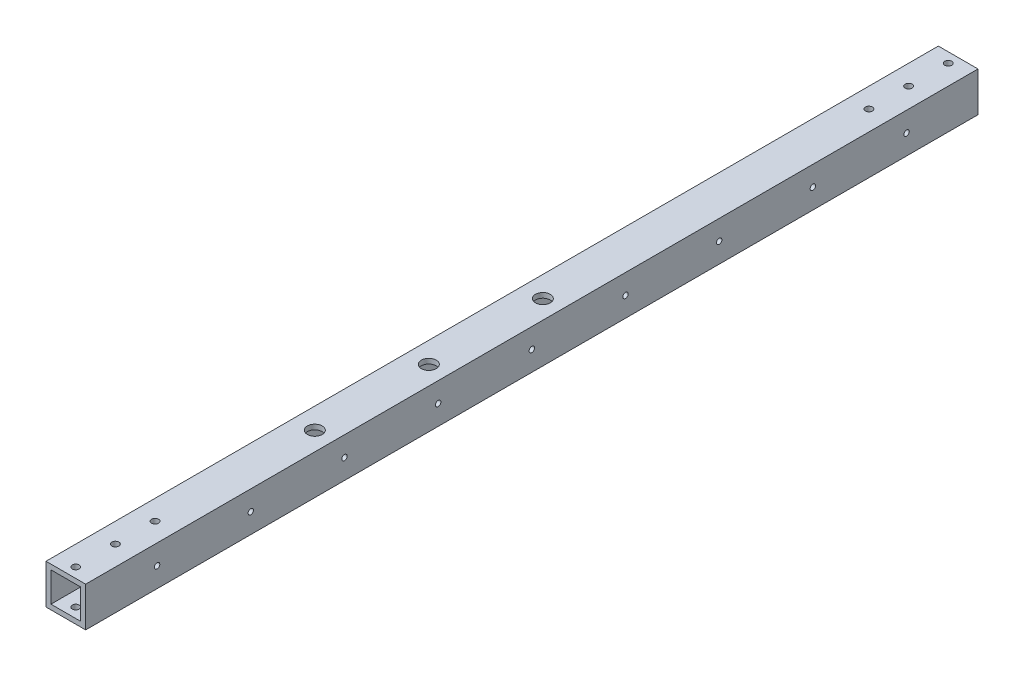
SolidWorks part; units mm, degrees
material "6061-T6 (SS)"
ref_plane "Front Plane" through (0, 0, 0) normal (0, 0, 1) x (1, 0, 0)
ref_plane "Top Plane" through (0, 0, 0) normal (0, 1, 0) x (1, 0, 0)
ref_plane "Right Plane" through (0, 0, 0) normal (1, 0, 0) x (0, 0, -1)
sketch "Sketch1" plane through (0, 0, 0) normal (0, 0, 1) x (1, 0, 0)
  line L1 (-12.7, -12.7) -> (12.7, -12.7)
  line L2 (-12.7, -12.7) -> (-12.7, 12.7)
  line L3 (-12.7, 12.7) -> (12.7, 12.7)
  line L4 (12.7, -12.7) -> (12.7, 12.7)
  line L5 (-12.7, -12.7) -> (12.7, 12.7) construction
  line L6 (-12.7, 12.7) -> (12.7, -12.7) construction
  point P0 (0, 0)
  dimension "D1" = 25.4
  dimension "D2" = 25.4
extrude "Extrude-Thin1" add sketch "Sketch1" along normal blind 571.5 thin thin type one direction reverse wall 3.175
hole_wizard "#8 Clearance Hole1" positions "3DSketch1" profile "Sketch3" hole size "#8" standard "ANSI Inch" end condition through all
sketch3d "3DSketch1"
  line L1 (12.7, 12.7, 0) -> (-12.7, 12.7, 0) construction
  line L6 (0, 12.7, 571.5) -> (0, 12.7, 0) construction
  line L7 (12.7, 12.7, 571.5) -> (-12.7, 12.7, 571.5) construction
  point P57 (0, 12.7, 6.35)
  point P59 (0, 12.7, 31.75)
  point P61 (0, 12.7, 57.15)
  point P63 (0, 12.7, 539.75)
  point P65 (0, 12.7, 514.35)
  point P67 (0, 12.7, 565.15)
  dimension "D1" = 25.4
  dimension "D2" = 25.4
  dimension "D3" = 6.35
  dimension "D4" = 25.4
  dimension "D5" = 25.4
  dimension "D6" = 6.35
sketch "Sketch3" plane through (0, 12.7, 565.15) normal (1, 0, 0) x (0, 0, 1)
  line L0 (0, 0) -> (0, 25.4)
  line L1 (0, 25.4) -> (2.2479, 25.4)
  line L2 (2.2479, 25.4) -> (2.2479, 0)
  line L5 (2.2479, 0) -> (0, 0)
  line L11 (0, -6.35) -> (0, 107.95) construction
  dimension "Thru Hole Dia." = 4.4958
  dimension "Thru Hole Depth" = 25.4
hole_wizard "#8-32 Tapped Hole1" positions "Sketch4" profile "Sketch5" tap size "#8-32" standard "ANSI Inch"
sketch "Sketch4" plane through (12.7, 82.55, 285.75) normal (1, 0, 0) x (0, 0, 1)
  point P0 (-300, 82.55)
  point P3 (-240, 82.55)
  point P6 (-180, 82.55)
  point P9 (-60, 82.55)
  point P12 (0, 82.55)
  point P15 (60, 82.55)
  point P18 (120, 82.55)
  point P21 (180, 82.55)
  point P24 (240, 82.55)
  point P27 (-120, 82.55)
  point P30 (-360, 82.55)
  point P33 (300, 82.55)
  point P36 (360, 82.55)
sketch "Sketch5" plane through (12.7, 0, -14.25) normal (0, 1, 0) x (0, 0, -1)
  line L0 (0, 0) -> (0, 11.7464)
  line L1 (0, 11.7464) -> (1.7272, 10.7086)
  line L2 (1.7272, 10.7086) -> (1.7272, 0)
  line L3 (1.7272, 0) -> (0, 0)
  line L4 (0, 11.7464) -> (-1.7272, 10.7086) construction
  line L5 (0, -6.35) -> (0, 107.95) construction
  dimension "Tap Drill Dia." = 3.4544
  dimension "Tap Drill Depth" = 10.7086
  dimension "Drill Angle" = 118
hole_wizard "3/8 (0.375) Diameter Hole2" positions "Sketch8" profile "Sketch9" hole size "3/8" standard "ANSI Inch" end condition through all
sketch "Sketch8" plane through (-346.075, -12.7, 285.75) normal (0, -1, 0) x (0, 0, 1)
  point P9 (-92.583, 346.075)
  point P12 (-35.433, 346.075)
  point P18 (35.814, 346.075)
  point P21 (92.964, 346.075)
  point P24 (-19.05, -346.775)
  point P27 (53.975, -346.775)
  point P30 (127, -346.775)
  point P42 (-381, -114.3)
  point P45 (-381, -130.175)
  point P48 (-381, -146.05)
  point P55 (-381, 114.3)
  point P58 (-381, 98.425)
  point P61 (-381, 82.55)
sketch "Sketch9" plane through (-692.15, -12.7, 193.167) normal (1, 0, 0) x (0, 0, -1)
  line L0 (0, 0) -> (0, 25.4)
  line L1 (0, 25.4) -> (4.7625, 25.4)
  line L2 (4.7625, 25.4) -> (4.7625, 0)
  line L3 (4.7625, 0) -> (0, 0)
  line L4 (0, -6.35) -> (0, 107.95) construction
  dimension "Thru Hole Dia." = 9.525
  dimension "Thru Hole Depth" = 25.4
